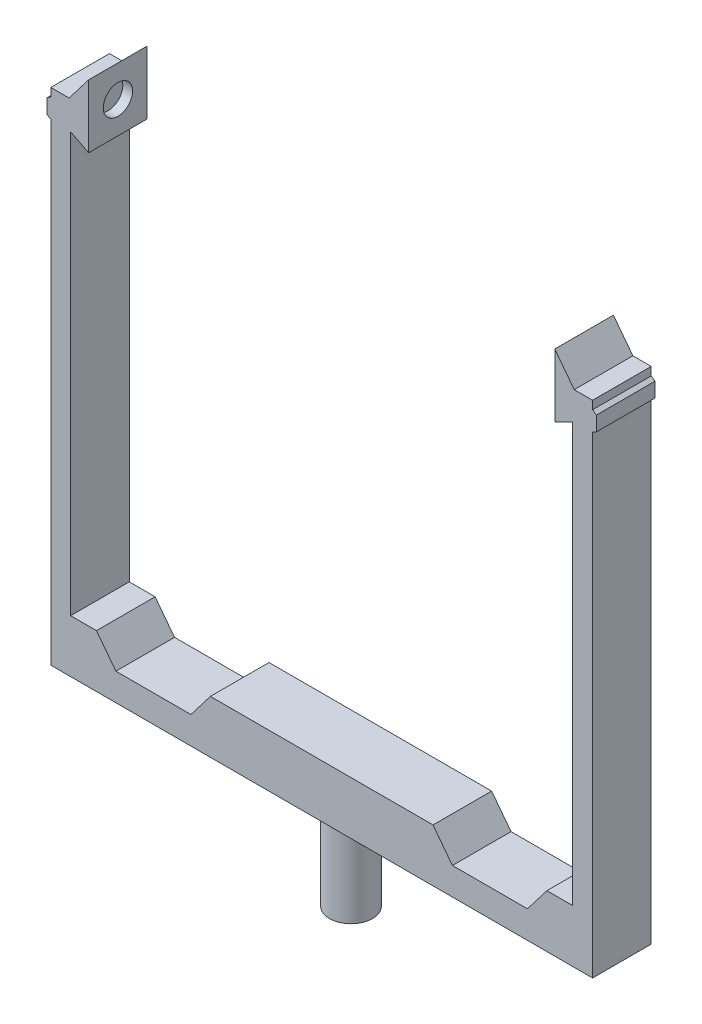
SolidWorks part; units mm, degrees
ref_plane "Front" through (0, 0, 0) normal (0, 0, 1) x (1, 0, 0)
ref_plane "Top" through (0, 0, 0) normal (0, 1, 0) x (1, 0, 0)
ref_plane "Right" through (0, 0, 0) normal (1, 0, 0) x (0, 0, -1)
sketch "Sketch1" plane through (0, 0, 0) normal (0, 0, 1) x (1, 0, 0)
  line L7 (50.3215, -242.2405) -> (164.2431, -242.2405)
  line L8 (164.2431, -242.2405) -> (174.1788, -255.2405)
  line L9 (174.1788, -255.2405) -> (212.5714, -255.2405)
  line L13 (235.7381, -27.8423) -> (226.5373, -32.526)
  line L14 (226.5373, -32.526) -> (226.5373, -0.2064)
  line L15 (226.5373, -0.2064) -> (236.499, -13.2405)
  line L16 (236.499, -13.2405) -> (245.8905, -13.2405)
  line L19 (245.8905, -27.2894) -> (245.8905, -269.2405)
  line L20 (245.8905, -269.2405) -> (-31.3259, -269.2405)
  line L26 (235.7381, -27.8423) -> (235.7381, -242.2405)
  line L27 (235.7381, -242.2405) -> (222.507, -242.2405)
  line L28 (245.8905, -13.2405) -> (245.8905, -17.4508)
  line L32 (212.5714, -255.2405) -> (222.507, -242.2405)
  line L33 (245.8905, -17.4508) -> (247.8386, -18.8259)
  line L34 (247.8386, -18.8259) -> (247.8386, -26.2977)
  line L35 (247.8386, -26.2977) -> (245.8905, -27.2894)
  line L36 (107.2823, -269.2405) -> (107.2823, -195.5793) construction
  line L37 (50.3215, -242.2405) -> (40.3858, -255.2405)
  line L38 (40.3858, -255.2405) -> (1.9932, -255.2405)
  line L39 (1.9932, -255.2405) -> (-7.9424, -242.2405)
  line L40 (-21.1735, -242.2405) -> (-7.9424, -242.2405)
  line L41 (-33.2739, -26.2977) -> (-31.3259, -27.2894)
  line L42 (-33.2739, -18.8259) -> (-33.2739, -26.2977)
  line L43 (-31.3259, -17.4508) -> (-33.2739, -18.8259)
  line L44 (-31.3259, -13.2405) -> (-31.3259, -17.4508)
  line L45 (-21.1735, -27.8423) -> (-21.1735, -242.2405)
  line L46 (-31.3259, -27.2894) -> (-31.3259, -269.2405)
  line L47 (-21.9344, -13.2405) -> (-31.3259, -13.2405)
  line L48 (-11.9727, -0.2064) -> (-21.9344, -13.2405)
  line L49 (-11.9727, -32.526) -> (-11.9727, -0.2064)
  line L50 (-21.1735, -27.8423) -> (-11.9727, -32.526)
  point P33 (107.2823, -242.2405)
  dimension "D1" = 238.51
  dimension "D2" = 256
  dimension "D3" = 27
  dimension "D4" = 27
  dimension "D5" = 14
extrude "Boss-Extrude1" add sketch "Sketch1" along normal blind 30 contours L36 L20 L19 L35 L34 L33 L28 L16 L15 L14 L13 L26 L27 L32 L9 L8 L7 | L20 L36 L7 L37 L38 L39 L40 L45 L50 L49 L48 L47 L44 L43 L42 L41 L46
sketch "Sketch2" plane through (0, -269.2405, 0) normal (0, -1, 0) x (1, 0, 0)
  line L0 (245.8905, 30) -> (-31.3259, 30) construction
  line L1 (-31.3259, 30) -> (-31.3259, 0) construction
  circle A0 centre (107.2823, 15) radius 11
  point P4 (107.2823, 30)
  point P7 (-31.3259, 15)
  dimension "D1" = 22
extrude "Boss-Extrude2" add sketch "Sketch2" along normal blind 45
sketch "Sketch3" plane through (-11.9727, 0, 0) normal (1, 0, 0) x (0, 0, -1)
  line L0 (-30, -0.2064) -> (0, -0.2064) construction
  line L1 (0, -32.526) -> (0, -0.2064) construction
  circle A0 centre (-15, -16.3662) radius 7.5
  point P2 (0, 0)
  point P5 (-15, -0.2064)
  point P8 (0, -16.3662)
  dimension "D1" = 15
extrude "Cut-Extrude1" cut sketch "Sketch3" against normal blind 5
sketch "Sketch4" plane through (226.5373, 0, 0) normal (-1, 0, 0) x (0, 0, 1)
  line L0 (30, -0.2064) -> (0, -0.2064) construction
  line L1 (0, -32.526) -> (0, -0.2064) construction
  circle A0 centre (15, -16.3662) radius 7.5
  point P4 (15, -0.2064)
  point P7 (0, -16.3662)
  dimension "D1" = 15
extrude "Cut-Extrude2" cut sketch "Sketch4" against normal blind 5
